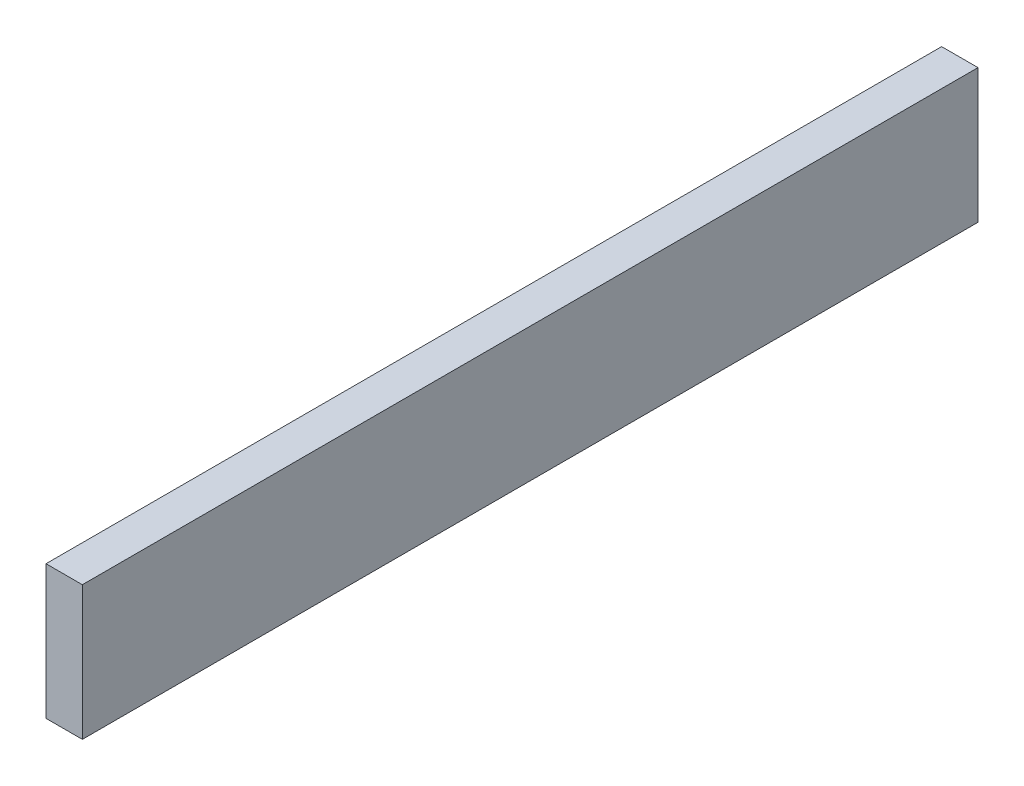
SolidWorks part; units mm, degrees
ref_plane "Front Plane" through (0, 0, 0) normal (0, 0, 1) x (1, 0, 0)
ref_plane "Top Plane" through (0, 0, 0) normal (0, 1, 0) x (1, 0, 0)
ref_plane "Right Plane" through (0, 0, 0) normal (1, 0, 0) x (0, 0, -1)
sketch "Sketch1" plane through (0, 0, 0) normal (1, 0, 0) x (0, 0, -1)
  line L1 (0, 0) -> (468, 0)
  line L2 (0, 0) -> (0, 70)
  line L3 (0, 70) -> (468, 70)
  line L4 (468, 0) -> (468, 70)
  dimension "D1" = 468
  dimension "D2" = 70
extrude "Boss-Extrude1" add sketch "Sketch1" along normal blind 19
